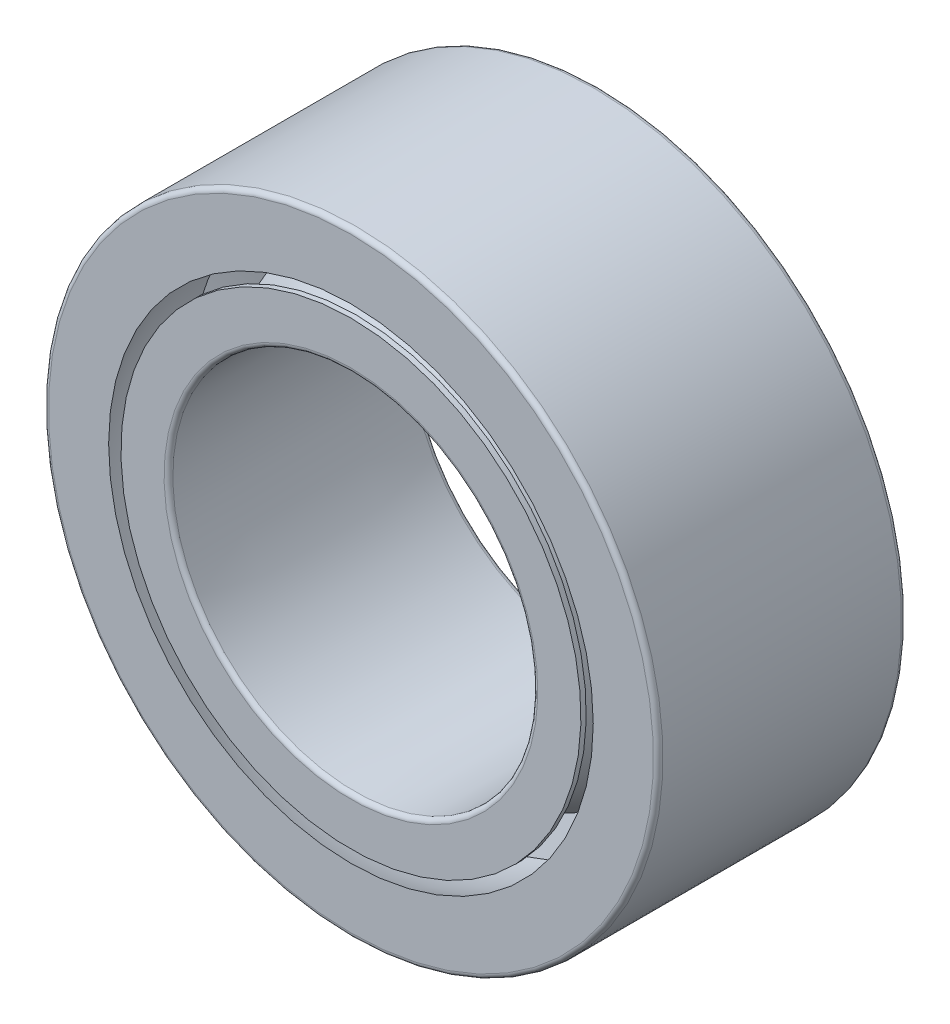
SolidWorks part; units mm, degrees
material "Cast Alloy Steel"
ref_plane "Front Plane" through (0, 0, 0) normal (0, 0, 1) x (1, 0, 0)
ref_plane "Top Plane" through (0, 0, 0) normal (0, 1, 0) x (1, 0, 0)
ref_plane "Right Plane" through (0, 0, 0) normal (1, 0, 0) x (0, 0, -1)
sketch "Sketch1" plane through (0, 0, 0) normal (1, 0, 0) x (0, 0, -1)
  line L2 (-109, 132.9) -> (-109, 106.4608)
  line L3 (-2.1, 135) -> (-106.9, 135)
  line L4 (0, 132.9) -> (0, 106.4608)
  line L5 (0, 0) -> (-154.3841, 0) construction
  line L6 (-107.227, 80.0256) -> (-2.1295, 81.5442)
  line L7 (-106.6582, 101.05) -> (-102.4339, 87.0655)
  line L10 (-62.7834, 99.0426) -> (-67.0076, 113.0271)
  line L11 (-106.6582, 101.05) -> (-109, 101.05)
  line L14 (-46.2166, 99.0426) -> (-41.9924, 113.0271)
  line L15 (-41.9924, 113.0271) -> (-67.0076, 113.0271)
  line L16 (-54.5, 119.6) -> (-54.5, 80.7875) construction
  line L17 (-2.3418, 101.05) -> (0, 101.05)
  line L18 (-6.5661, 87.0655) -> (-2.3418, 101.05)
  line L20 (0, 101.05) -> (-0.0598, 83.6368)
  line L21 (-109, 101.05) -> (-109, 82.1)
  arc A0 (-0.0598, 83.6368) -> (-2.1295, 81.5442) centre (-2.1598, 83.644) cw
  arc A1 (-102.4339, 87.0655) -> (-62.7834, 99.0426) centre (-116.6701, 205.8151) ccw
  arc A2 (-106.9, 135) -> (-109, 132.9) centre (-106.9, 132.9) ccw
  arc A3 (-6.5661, 87.0655) -> (-46.2166, 99.0426) centre (7.6701, 205.8151) cw
  arc A5 (-109, 82.1) -> (-107.227, 80.0256) centre (-106.9, 82.1) ccw
  arc A6 (0, 132.9) -> (-2.1, 135) centre (-2.1, 132.9) ccw
  arc A10 (0, 106.4608) -> (-109, 106.4608) centre (-54.5, 0) ccw
  dimension "D1" = 2.1
  dimension "D2" = 2.1
  dimension "D3" = 105.0975
revolve "Revolve1" add sketch "Sketch1" angle 360 about L5
ref_plane "Plane1" through (0, 0, 54.5) normal (0, 0, 1) x (1, 0, 0)
scale "Scale1" bodies to scale 117 119 scale about origin uniform scaling yes scale factor 0.1
ref_point "Point1"
ref_point "Point2"
sketch "Sketch3" plane through (0, 0, 0) normal (1, 0, 0) x (0, 0, -1)
  line L0 (-10.69, -13.5) -> (-0.21, -13.5) construction
  point P0 (-5.45, -13.5)
  point P1 (3.4458, 4.1238)
  point P4 (-21.4049, 3.9077)
sketch "Sketch5" plane through (0, 0, 0) normal (1, 0, 0) x (0, 0, -1)
  line L0 (-10.9, 1.8208) -> (0, 1.8208) construction
  line L1 (-10.9, 13.29) -> (-10.9, -13.29) construction
  line L2 (0, -13.29) -> (0, 13.29) construction
